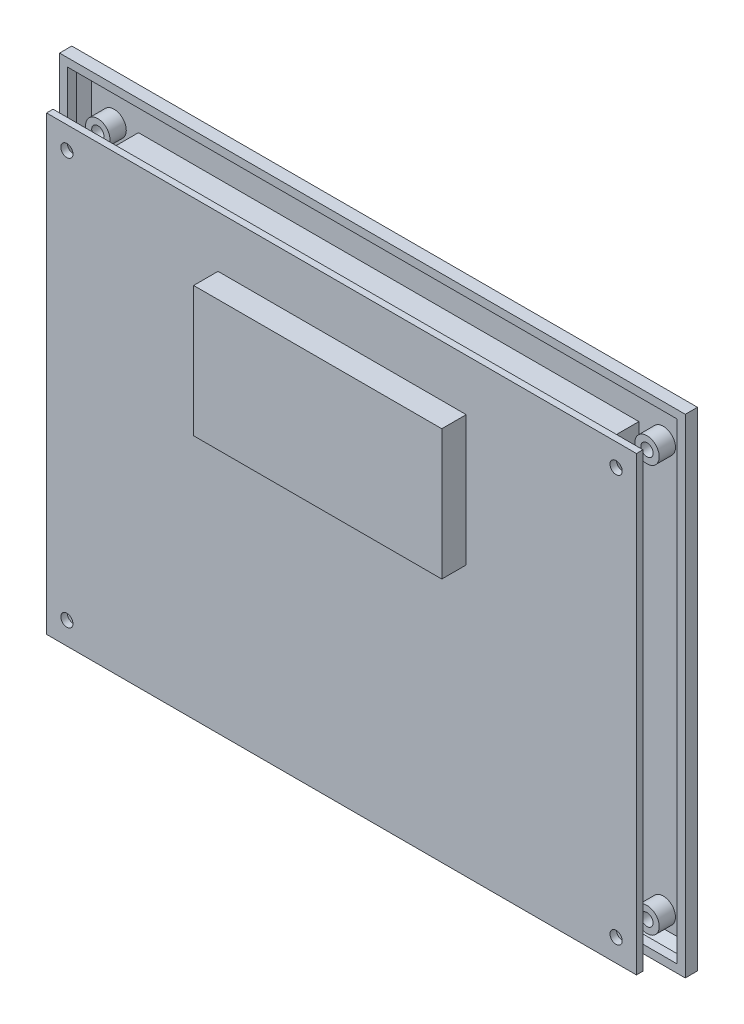
SolidWorks part; units mm, degrees
ref_plane "前视基准面" through (0, 0, 0) normal (0, 0, 1) x (1, 0, 0)
ref_plane "上视基准面" through (0, 0, 0) normal (0, 1, 0) x (1, 0, 0)
ref_plane "右视基准面" through (0, 0, 0) normal (1, 0, 0) x (0, 0, -1)
sketch "草图1" plane through (0, 0, 0) normal (0, 0, 1) x (1, 0, 0)
  line L0 (-105.28, 0) -> (132.6255, 0) construction
  line L1 (-76.9, 60) -> (76.9, 60)
  line L2 (-76.9, 60) -> (-76.9, -60)
  line L3 (-76.9, -60) -> (76.9, -60)
  line L4 (76.9, 60) -> (76.9, -60)
  line L5 (0, -67.3252) -> (0, 121.7491) construction
  line L7 (56.75, 40.5) -> (-56.75, 40.5)
  line L8 (56.75, 40.5) -> (56.75, -45)
  line L9 (56.75, -45) -> (-56.75, -45)
  line L10 (-56.75, 40.5) -> (-56.75, -45)
  dimension "D1" = 153.8
  dimension "D2" = 120
  dimension "D3" = 85.5
  dimension "D4" = 113.5
  dimension "D5" = 19.5
extrude "凸台-拉伸1" add sketch "草图1" along normal blind 6
chamfer "倒角1" distance 3 angle 45 8 edges at (0, 40.5, 0) (-56.75, -2.25, 0) (56.75, -2.25, 0) (0, -45, 0) (0, -60, 0) (76.9, 0, 0) (-76.9, 0, 0) (0, 60, 0)
shell "抽壳1" thickness 2
sketch "草图3" plane through (0, 0, 6) normal (0, 0, 1) x (1, 0, 0)
  line L2 (-60.5784, 44.3284) -> (60.5784, 44.3284)
  line L3 (-60.5784, 44.3284) -> (-60.5784, -48.8284)
  line L4 (-60.5784, -48.8284) -> (60.5784, -48.8284)
  line L5 (60.5784, 44.3284) -> (60.5784, -48.8284)
extrude "切除-拉伸1" cut sketch "草图3" against normal offset from surface (4 mm away) 2 up to face at (0, -2.25, 0)
sketch "草图4" plane through (0, 0, 2) normal (0, 0, 1) x (1, 0, 0)
  line L0 (-93.373, -2.25) -> (105.0602, -2.25) construction
  line L1 (0, 87.1984) -> (0, -85.1163) construction
  line L2 (57.75, 41.5) -> (-57.75, 41.5) construction
  line L3 (-57.75, -46) -> (57.75, -46) construction
  circle A0 centre (-67.5, 47.75) radius 1.5
  circle A1 centre (-67.5, 47.75) radius 3
  circle A2 centre (67.5, 47.75) radius 3
  circle A3 centre (67.5, 47.75) radius 1.5
  circle A4 centre (67.5, -52.25) radius 1.5
  circle A5 centre (67.5, -52.25) radius 3
  circle A6 centre (-67.5, -52.25) radius 3
  circle A7 centre (-67.5, -52.25) radius 1.5
  point P19 (-58.0527, -47.6585)
  dimension "D1" = 3
  dimension "D2" = 6
  dimension "D3" = 135
  dimension "D4" = 100
extrude "凸台-拉伸3" add sketch "草图4" along normal up to surface (4 mm away) up to face at (0, 0, 6)
sketch "草图2" plane through (0, 0, 2) normal (0, 0, 1) x (1, 0, 0)
  line L0 (0, 78.8154) -> (0, -71.9767) construction
  line L1 (-61.5, 48.75) -> (61.5, 48.75)
  line L2 (-61.5, 48.75) -> (-61.5, -53.25)
  line L3 (-61.5, -53.25) -> (61.5, -53.25)
  line L4 (61.5, 48.75) -> (61.5, -53.25)
  line L5 (-94.8595, -2.25) -> (96.4128, -2.25) construction
  line L6 (57.75, 41.5) -> (-57.75, 41.5) construction
  line L7 (-57.75, -46) -> (57.75, -46) construction
  dimension "D1" = 102
  dimension "D2" = 123
extrude "凸台-拉伸2" add sketch "草图2" along normal blind 10
sketch "草图5" plane through (0, 0, 12) normal (0, 0, 1) x (1, 0, 0)
  line L0 (0, 77.3908) -> (0, -81.3058) construction
  line L1 (-72.5, 53.25) -> (72.5, 53.25)
  line L2 (-72.5, 53.25) -> (-72.5, -57.75)
  line L3 (-72.5, -57.75) -> (72.5, -57.75)
  line L4 (72.5, 53.25) -> (72.5, -57.75)
  line L5 (-103.7339, -2.25) -> (97.8132, -2.25) construction
  line L6 (61.5, 48.75) -> (-61.5, 48.75) construction
  line L7 (-61.5, -53.25) -> (61.5, -53.25) construction
  dimension "D1" = 145
  dimension "D2" = 111
extrude "凸台-拉伸4" add sketch "草图5" along normal blind 1.6
sketch "草图6" plane through (0, 0, 13.6) normal (0, 0, 1) x (1, 0, 0)
  circle A0 centre (-67.5, 47.75) radius 1.5 construction
  circle A1 centre (67.5, 47.75) radius 1.5 construction
  circle A2 centre (67.5, -52.25) radius 1.5 construction
  circle A3 centre (-67.5, -52.25) radius 1.5 construction
  circle A4 centre (-67.5, 47.75) radius 1.5
  circle A5 centre (67.5, 47.75) radius 1.5
  circle A6 centre (67.5, -52.25) radius 1.5
  circle A7 centre (-67.5, -52.25) radius 1.5
extrude "切除-拉伸2" cut sketch "草图6" against normal blind 1.6
sketch "草图7" plane through (0, 0, 13.6) normal (0, 0, 1) x (1, 0, 0)
  line L1 (-30.3465, 40.6044) -> (30.6535, 40.6044)
  line L2 (-30.3465, 40.6044) -> (-30.3465, 8.6044)
  line L3 (-30.3465, 8.6044) -> (30.6535, 8.6044)
  line L4 (30.6535, 40.6044) -> (30.6535, 8.6044)
  dimension "D1" = 61
  dimension "D2" = 32
extrude "凸台-拉伸5" add sketch "草图7" along normal blind 6
